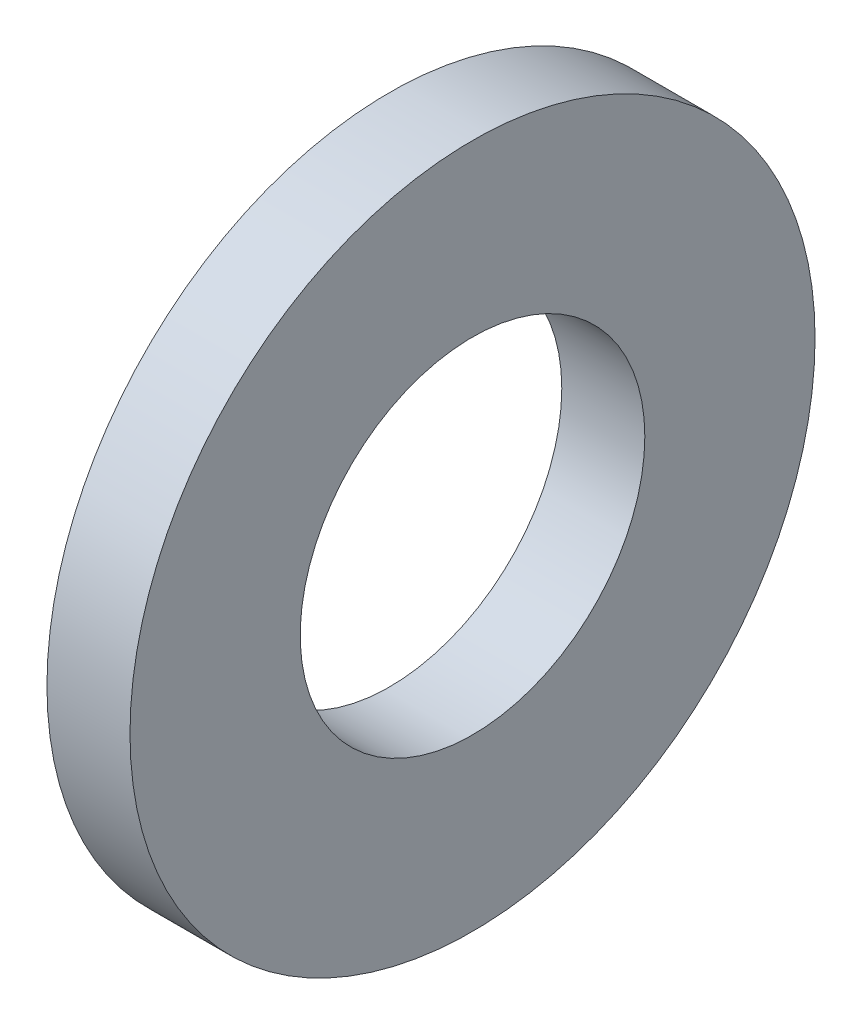
SolidWorks part; units mm, degrees
material "ABS"
ref_plane "前视基准面" through (0, 0, 0) normal (0, 0, 1) x (1, 0, 0)
ref_plane "上视基准面" through (0, 0, 0) normal (0, 1, 0) x (1, 0, 0)
ref_plane "右视基准面" through (0, 0, 0) normal (1, 0, 0) x (0, 0, -1)
other "Configuration Table"
sketch "草图1" plane through (0, 0, 0) normal (1, 0, 0) x (0, 0, -1)
  circle A0 centre (0, 0) radius 4.15
  circle A1 centre (0, 0) radius 8.25
  dimension "D1" = 8.3
  dimension "D2" = 16.5
extrude "凸台-拉伸1" add sketch "草图1" along normal blind 2
